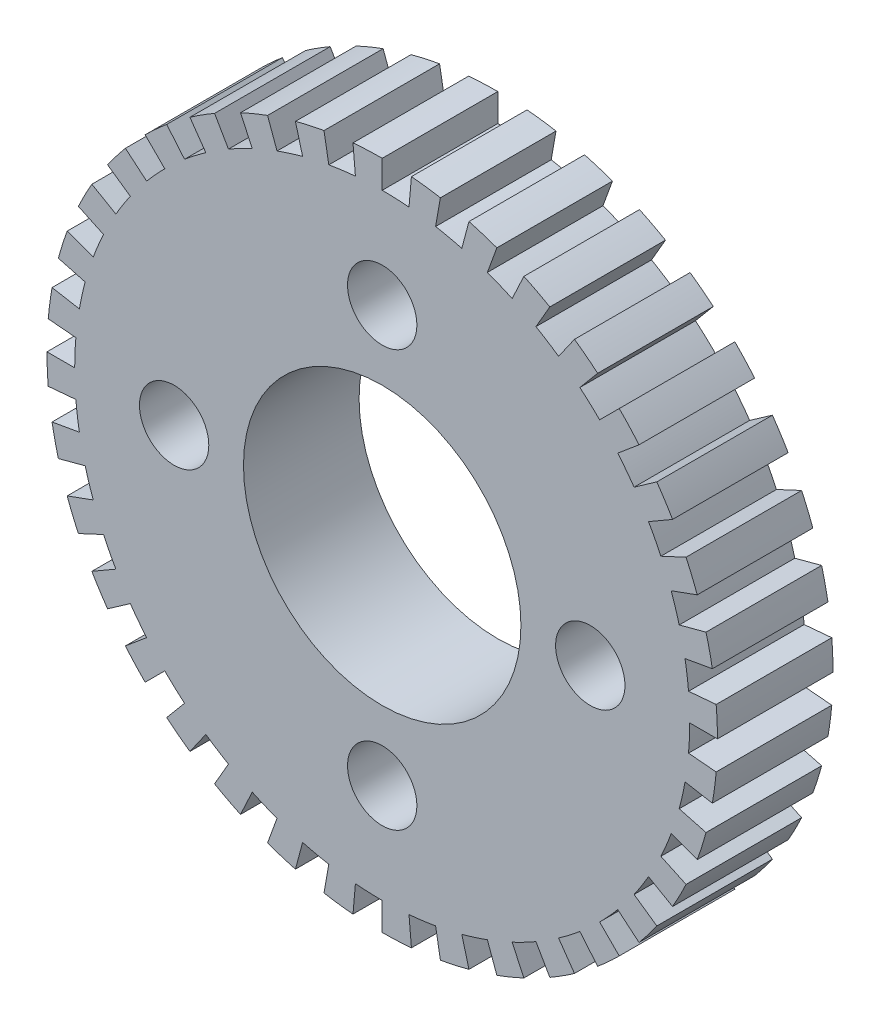
SolidWorks part; units mm, degrees
ref_plane "前视基准面" through (0, 0, 0) normal (0, 0, 1) x (1, 0, 0)
ref_plane "上视基准面" through (0, 0, 0) normal (0, 1, 0) x (1, 0, 0)
ref_plane "右视基准面" through (0, 0, 0) normal (1, 0, 0) x (0, 0, -1)
sketch "草图1" plane through (0, 0, 0) normal (0, 0, 1) x (1, 0, 0)
  line L0 (26.1959, -4.619) -> (28.5594, -5.0358)
  line L1 (26.4988, -2.3183) -> (28.8896, -2.5275)
  line L2 (24.9958, -9.0977) -> (27.2511, -9.9186)
  line L3 (26.6, 0) -> (29, 0)
  line L4 (26.4988, 2.3183) -> (28.8896, 2.5275)
  line L6 (25.6936, -6.8846) -> (28.0118, -7.5058)
  line L7 (23.0363, -13.3) -> (25.1147, -14.5)
  line L8 (24.1078, -11.2416) -> (26.2829, -12.2559)
  line L9 (20.3768, -17.0982) -> (22.2153, -18.6408)
  line L10 (21.7894, -15.2571) -> (23.7554, -16.6337)
  line L11 (17.0982, -20.3768) -> (18.6408, -22.2153)
  line L12 (18.809, -18.809) -> (20.5061, -20.5061)
  line L13 (13.3, -23.0363) -> (14.5, -25.1147)
  line L14 (15.2571, -21.7894) -> (16.6337, -23.7554)
  line L15 (9.0977, -24.9958) -> (9.9186, -27.2511)
  line L16 (11.2416, -24.1078) -> (12.2559, -26.2829)
  line L17 (4.619, -26.1959) -> (5.0358, -28.5594)
  line L18 (6.8846, -25.6936) -> (7.5058, -28.0118)
  line L19 (0, -26.6) -> (0, -29)
  line L20 (2.3183, -26.4988) -> (2.5275, -28.8896)
  line L21 (-4.619, -26.1959) -> (-5.0358, -28.5594)
  line L22 (-2.3183, -26.4988) -> (-2.5275, -28.8896)
  line L23 (-9.0977, -24.9958) -> (-9.9186, -27.2511)
  line L24 (-6.8846, -25.6936) -> (-7.5058, -28.0118)
  line L25 (-13.3, -23.0363) -> (-14.5, -25.1147)
  line L26 (-11.2416, -24.1078) -> (-12.2559, -26.2829)
  line L27 (-17.0982, -20.3768) -> (-18.6408, -22.2153)
  line L28 (-15.2571, -21.7894) -> (-16.6337, -23.7554)
  line L29 (-20.3768, -17.0982) -> (-22.2153, -18.6408)
  line L30 (-18.809, -18.809) -> (-20.5061, -20.5061)
  line L31 (-23.0363, -13.3) -> (-25.1147, -14.5)
  line L32 (-21.7894, -15.2571) -> (-23.7554, -16.6337)
  line L33 (-24.9958, -9.0977) -> (-27.2511, -9.9186)
  line L34 (-24.1078, -11.2416) -> (-26.2829, -12.2559)
  line L35 (-26.1959, -4.619) -> (-28.5594, -5.0358)
  line L36 (-25.6936, -6.8846) -> (-28.0118, -7.5058)
  line L37 (-26.6, 0) -> (-29, 0)
  line L38 (-26.4988, -2.3183) -> (-28.8896, -2.5275)
  line L39 (-26.1959, 4.619) -> (-28.5594, 5.0358)
  line L40 (-26.4988, 2.3183) -> (-28.8896, 2.5275)
  line L41 (-24.9958, 9.0977) -> (-27.2511, 9.9186)
  line L42 (-25.6936, 6.8846) -> (-28.0118, 7.5058)
  line L43 (-23.0363, 13.3) -> (-25.1147, 14.5)
  line L44 (-24.1078, 11.2416) -> (-26.2829, 12.2559)
  line L45 (-20.3768, 17.0982) -> (-22.2153, 18.6408)
  line L46 (-21.7894, 15.2571) -> (-23.7554, 16.6337)
  line L47 (-17.0982, 20.3768) -> (-18.6408, 22.2153)
  line L48 (-18.809, 18.809) -> (-20.5061, 20.5061)
  line L49 (-13.3, 23.0363) -> (-14.5, 25.1147)
  line L50 (-15.2571, 21.7894) -> (-16.6337, 23.7554)
  line L51 (-9.0977, 24.9958) -> (-9.9186, 27.2511)
  line L52 (-11.2416, 24.1078) -> (-12.2559, 26.2829)
  line L53 (-4.619, 26.1959) -> (-5.0358, 28.5594)
  line L54 (-6.8846, 25.6936) -> (-7.5058, 28.0118)
  line L55 (0, 26.6) -> (0, 29)
  line L56 (-2.3183, 26.4988) -> (-2.5275, 28.8896)
  line L57 (4.619, 26.1959) -> (5.0358, 28.5594)
  line L58 (2.3183, 26.4988) -> (2.5275, 28.8896)
  line L59 (9.0977, 24.9958) -> (9.9186, 27.2511)
  line L60 (6.8846, 25.6936) -> (7.5058, 28.0118)
  line L61 (13.3, 23.0363) -> (14.5, 25.1147)
  line L62 (11.2416, 24.1078) -> (12.2559, 26.2829)
  line L63 (17.0982, 20.3768) -> (18.6408, 22.2153)
  line L64 (15.2571, 21.7894) -> (16.6337, 23.7554)
  line L65 (20.3768, 17.0982) -> (22.2153, 18.6408)
  line L66 (18.809, 18.809) -> (20.5061, 20.5061)
  line L67 (23.0363, 13.3) -> (25.1147, 14.5)
  line L68 (21.7894, 15.2571) -> (23.7554, 16.6337)
  line L69 (24.9958, 9.0977) -> (27.2511, 9.9186)
  line L70 (24.1078, 11.2416) -> (26.2829, 12.2559)
  line L71 (26.1959, 4.619) -> (28.5594, 5.0358)
  line L72 (25.6936, 6.8846) -> (28.0118, 7.5058)
  circle A0 centre (0, 0) radius 12
  arc A1 (29, 0) -> (28.8896, 2.5275) centre (0, 0) ccw
  arc A2 (26.4988, 2.3183) -> (26.1959, 4.619) centre (0, 0) ccw
  arc A3 (28.5594, -5.0358) -> (28.8896, -2.5275) centre (0, 0) ccw
  arc A4 (26.4988, -2.3183) -> (26.6, 0) centre (0, 0) ccw
  arc A5 (27.2511, -9.9186) -> (28.0118, -7.5058) centre (0, 0) ccw
  arc A6 (25.6936, -6.8846) -> (26.1959, -4.619) centre (0, 0) ccw
  arc A7 (25.1147, -14.5) -> (26.2829, -12.2559) centre (0, 0) ccw
  arc A8 (24.1078, -11.2416) -> (24.9958, -9.0977) centre (0, 0) ccw
  arc A9 (22.2153, -18.6408) -> (23.7554, -16.6337) centre (0, 0) ccw
  arc A10 (21.7894, -15.2571) -> (23.0363, -13.3) centre (0, 0) ccw
  arc A11 (18.6408, -22.2153) -> (20.5061, -20.5061) centre (0, 0) ccw
  arc A12 (18.809, -18.809) -> (20.3768, -17.0982) centre (0, 0) ccw
  arc A13 (14.5, -25.1147) -> (16.6337, -23.7554) centre (0, 0) ccw
  arc A14 (15.2571, -21.7894) -> (17.0982, -20.3768) centre (0, 0) ccw
  arc A15 (9.9186, -27.2511) -> (12.2559, -26.2829) centre (0, 0) ccw
  arc A16 (11.2416, -24.1078) -> (13.3, -23.0363) centre (0, 0) ccw
  arc A17 (5.0358, -28.5594) -> (7.5058, -28.0118) centre (0, 0) ccw
  arc A18 (6.8846, -25.6936) -> (9.0977, -24.9958) centre (0, 0) ccw
  arc A19 (0, -29) -> (2.5275, -28.8896) centre (0, 0) ccw
  arc A20 (2.3183, -26.4988) -> (4.619, -26.1959) centre (0, 0) ccw
  arc A21 (-5.0358, -28.5594) -> (-2.5275, -28.8896) centre (0, 0) ccw
  arc A22 (-2.3183, -26.4988) -> (0, -26.6) centre (0, 0) ccw
  arc A23 (-9.9186, -27.2511) -> (-7.5058, -28.0118) centre (0, 0) ccw
  arc A24 (-6.8846, -25.6936) -> (-4.619, -26.1959) centre (0, 0) ccw
  arc A25 (-14.5, -25.1147) -> (-12.2559, -26.2829) centre (0, 0) ccw
  arc A26 (-11.2416, -24.1078) -> (-9.0977, -24.9958) centre (0, 0) ccw
  arc A27 (-18.6408, -22.2153) -> (-16.6337, -23.7554) centre (0, 0) ccw
  arc A28 (-15.2571, -21.7894) -> (-13.3, -23.0363) centre (0, 0) ccw
  arc A29 (-22.2153, -18.6408) -> (-20.5061, -20.5061) centre (0, 0) ccw
  arc A30 (-18.809, -18.809) -> (-17.0982, -20.3768) centre (0, 0) ccw
  arc A31 (-25.1147, -14.5) -> (-23.7554, -16.6337) centre (0, 0) ccw
  arc A32 (-21.7894, -15.2571) -> (-20.3768, -17.0982) centre (0, 0) ccw
  arc A33 (-27.2511, -9.9186) -> (-26.2829, -12.2559) centre (0, 0) ccw
  arc A34 (-24.1078, -11.2416) -> (-23.0363, -13.3) centre (0, 0) ccw
  arc A35 (-28.5594, -5.0358) -> (-28.0118, -7.5058) centre (0, 0) ccw
  arc A36 (-25.6936, -6.8846) -> (-24.9958, -9.0977) centre (0, 0) ccw
  arc A37 (-29, 0) -> (-28.8896, -2.5275) centre (0, 0) ccw
  arc A38 (-26.4988, -2.3183) -> (-26.1959, -4.619) centre (0, 0) ccw
  arc A39 (-28.5594, 5.0358) -> (-28.8896, 2.5275) centre (0, 0) ccw
  arc A40 (-26.4988, 2.3183) -> (-26.6, 0) centre (0, 0) ccw
  arc A41 (-27.2511, 9.9186) -> (-28.0118, 7.5058) centre (0, 0) ccw
  arc A42 (-25.6936, 6.8846) -> (-26.1959, 4.619) centre (0, 0) ccw
  arc A43 (-25.1147, 14.5) -> (-26.2829, 12.2559) centre (0, 0) ccw
  arc A44 (-24.1078, 11.2416) -> (-24.9958, 9.0977) centre (0, 0) ccw
  arc A45 (-22.2153, 18.6408) -> (-23.7554, 16.6337) centre (0, 0) ccw
  arc A46 (-21.7894, 15.2571) -> (-23.0363, 13.3) centre (0, 0) ccw
  arc A47 (-18.6408, 22.2153) -> (-20.5061, 20.5061) centre (0, 0) ccw
  arc A48 (-18.809, 18.809) -> (-20.3768, 17.0982) centre (0, 0) ccw
  arc A49 (-14.5, 25.1147) -> (-16.6337, 23.7554) centre (0, 0) ccw
  arc A50 (-15.2571, 21.7894) -> (-17.0982, 20.3768) centre (0, 0) ccw
  arc A51 (-9.9186, 27.2511) -> (-12.2559, 26.2829) centre (0, 0) ccw
  arc A52 (-11.2416, 24.1078) -> (-13.3, 23.0363) centre (0, 0) ccw
  arc A53 (-5.0358, 28.5594) -> (-7.5058, 28.0118) centre (0, 0) ccw
  arc A54 (-6.8846, 25.6936) -> (-9.0977, 24.9958) centre (0, 0) ccw
  arc A55 (0, 29) -> (-2.5275, 28.8896) centre (0, 0) ccw
  arc A56 (-2.3183, 26.4988) -> (-4.619, 26.1959) centre (0, 0) ccw
  arc A57 (5.0358, 28.5594) -> (2.5275, 28.8896) centre (0, 0) ccw
  arc A58 (2.3183, 26.4988) -> (0, 26.6) centre (0, 0) ccw
  arc A59 (9.9186, 27.2511) -> (7.5058, 28.0118) centre (0, 0) ccw
  arc A60 (6.8846, 25.6936) -> (4.619, 26.1959) centre (0, 0) ccw
  arc A61 (14.5, 25.1147) -> (12.2559, 26.2829) centre (0, 0) ccw
  arc A62 (11.2416, 24.1078) -> (9.0977, 24.9958) centre (0, 0) ccw
  arc A63 (18.6408, 22.2153) -> (16.6337, 23.7554) centre (0, 0) ccw
  arc A64 (15.2571, 21.7894) -> (13.3, 23.0363) centre (0, 0) ccw
  arc A65 (22.2153, 18.6408) -> (20.5061, 20.5061) centre (0, 0) ccw
  arc A66 (18.809, 18.809) -> (17.0982, 20.3768) centre (0, 0) ccw
  arc A67 (25.1147, 14.5) -> (23.7554, 16.6337) centre (0, 0) ccw
  arc A68 (21.7894, 15.2571) -> (20.3768, 17.0982) centre (0, 0) ccw
  arc A69 (27.2511, 9.9186) -> (26.2829, 12.2559) centre (0, 0) ccw
  arc A70 (24.1078, 11.2416) -> (23.0363, 13.3) centre (0, 0) ccw
  arc A71 (28.5594, 5.0358) -> (28.0118, 7.5058) centre (0, 0) ccw
  arc A72 (25.6936, 6.8846) -> (24.9958, 9.0977) centre (0, 0) ccw
  point P11 (0, 0)
  point P187 (0, 0)
  dimension "D1" = 36
extrude "凸台-拉伸1" add sketch "草图1" along normal blind 10
sketch "草图2" plane through (0, 0, 0) normal (0, 0, 1) x (1, 0, 0)
  circle A1 centre (18, 0) radius 3
  circle A2 centre (0, -18) radius 3
  circle A3 centre (-18, 0) radius 3
  circle A4 centre (0, 18) radius 3
  point P12 (0, 0)
  dimension "D1" = 4
extrude "切除-拉伸1" cut sketch "草图2" along normal blind 10
